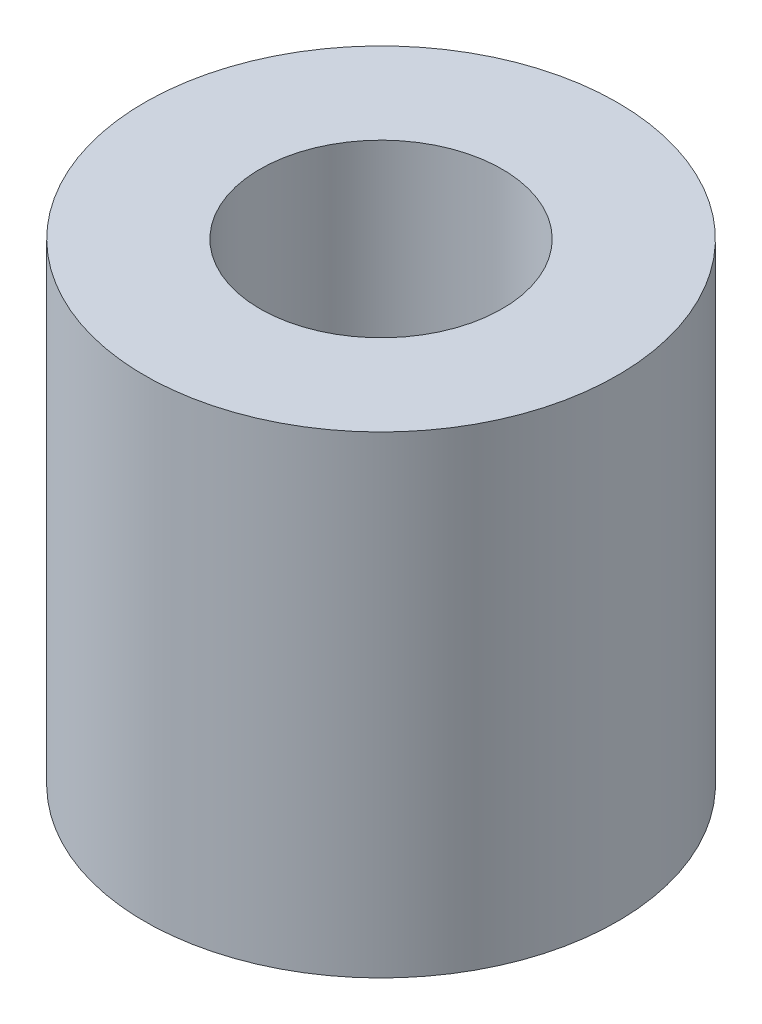
SolidWorks part; units mm, degrees
ref_plane "Front Plane" through (0, 0, 0) normal (0, 0, 1) x (1, 0, 0)
ref_plane "Top Plane" through (0, 0, 0) normal (0, 1, 0) x (1, 0, 0)
ref_plane "Right Plane" through (0, 0, 0) normal (1, 0, 0) x (0, 0, -1)
sketch "Sketch1" plane through (0, 0, 0) normal (0, 0, 1) x (1, 0, 0)
  line L0 (0, 0) -> (0, 4.8674) construction
  line L2 (0, 0) -> (2.3813, 0)
  line L3 (0, 0) -> (0, 4.7625)
  line L4 (0, 4.7625) -> (2.3813, 4.7625)
  line L5 (2.3813, 0) -> (2.3813, 4.7625)
  line L6 (0, 0) -> (2.3813, 4.7625) construction
  line L7 (0, 4.7625) -> (2.3813, 0) construction
  point P7 (1.1906, 2.3812)
  dimension "D1" = 4.7625
  dimension "D2" = 4.7625
revolve "Revolve1" add sketch "Sketch1" angle 360 about L0
hole_wizard "#2 Clearance Hole1" positions "Sketch2" profile "Sketch3" hole size "#2" standard "ANSI Inch" end condition through all
sketch "Sketch2" plane through (0, 4.7625, 0) normal (0, 1, 0) x (1, 0, 0)
  point P0 (0, 0)
sketch "Sketch3" plane through (0, 4.7625, 0) normal (1, 0, 0) x (0, 0, 1)
  line L0 (0, 0) -> (0, 4.7625)
  line L1 (0, 4.7625) -> (1.2192, 4.7625)
  line L2 (1.2192, 4.7625) -> (1.2192, 0)
  line L5 (1.2192, 0) -> (0, 0)
  line L11 (0, -6.35) -> (0, 107.95) construction
  dimension "Thru Hole Dia." = 2.4384
  dimension "Thru Hole Depth" = 4.7625
